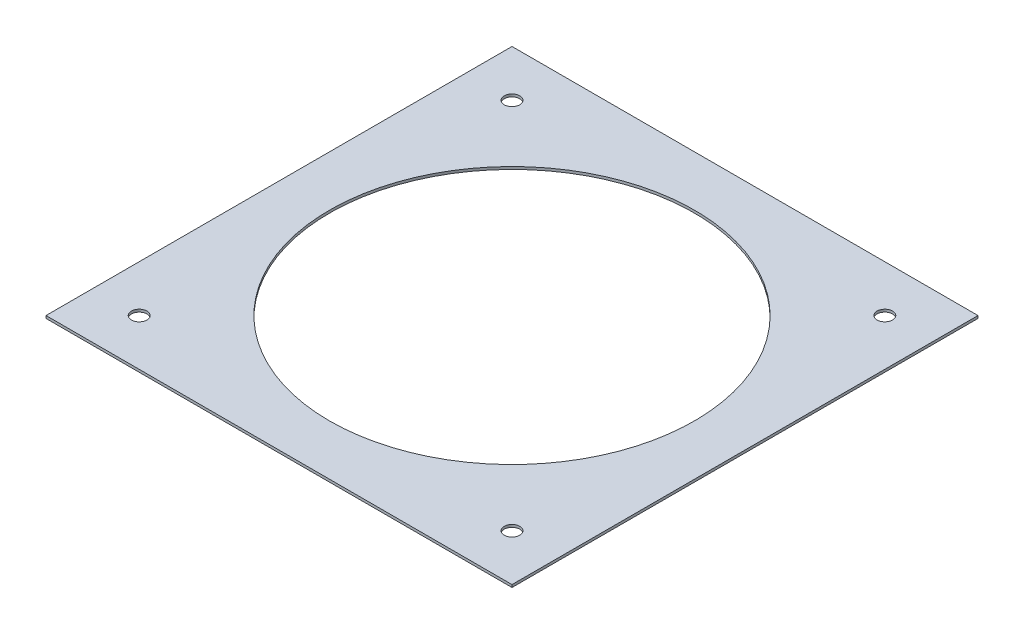
SolidWorks part; units mm, degrees
ref_plane "Front Plane" through (0, 0, 0) normal (0, 0, 1) x (1, 0, 0)
ref_plane "Top Plane" through (0, 0, 0) normal (0, 1, 0) x (1, 0, 0)
ref_plane "Right Plane" through (0, 0, 0) normal (1, 0, 0) x (0, 0, -1)
sketch "Sketch1" plane through (0, 0, 0) normal (0, 1, 0) x (1, 0, 0)
  line L1 (-76.2, -76.2) -> (76.2, -76.2)
  line L2 (-76.2, -76.2) -> (-76.2, 76.2)
  line L3 (-76.2, 76.2) -> (76.2, 76.2)
  line L4 (76.2, -76.2) -> (76.2, 76.2)
  line L5 (-76.2, -76.2) -> (76.2, 76.2) construction
  line L6 (-76.2, 76.2) -> (76.2, -76.2) construction
  circle A0 centre (0, 0) radius 59.69
  dimension "D1" = 119.38
  dimension "D2" = 152.4
  dimension "D3" = 152.4
extrude "Boss-Extrude1" add sketch "Sketch1" along normal mid plane 0.8382
sketch "Sketch2" plane through (0, 0.4191, 0) normal (0, 1, 0) x (1, 0, 0)
  line L0 (-76.2, 76.2) -> (-76.2, -76.2) construction
  line L1 (76.2, 76.2) -> (-76.2, 76.2) construction
  circle A0 centre (-60.96, 60.96) radius 2.54
  dimension "D1" = 5.08
  dimension "D2" = 15.24
  dimension "D3" = 15.24
extrude "Cut-Extrude1" cut sketch "Sketch2" against normal through all
pattern_circular "CirPattern1" count 4 over 360 about axis through (0, 0, 0) along (0, 1, 0) of "Cut-Extrude1"
